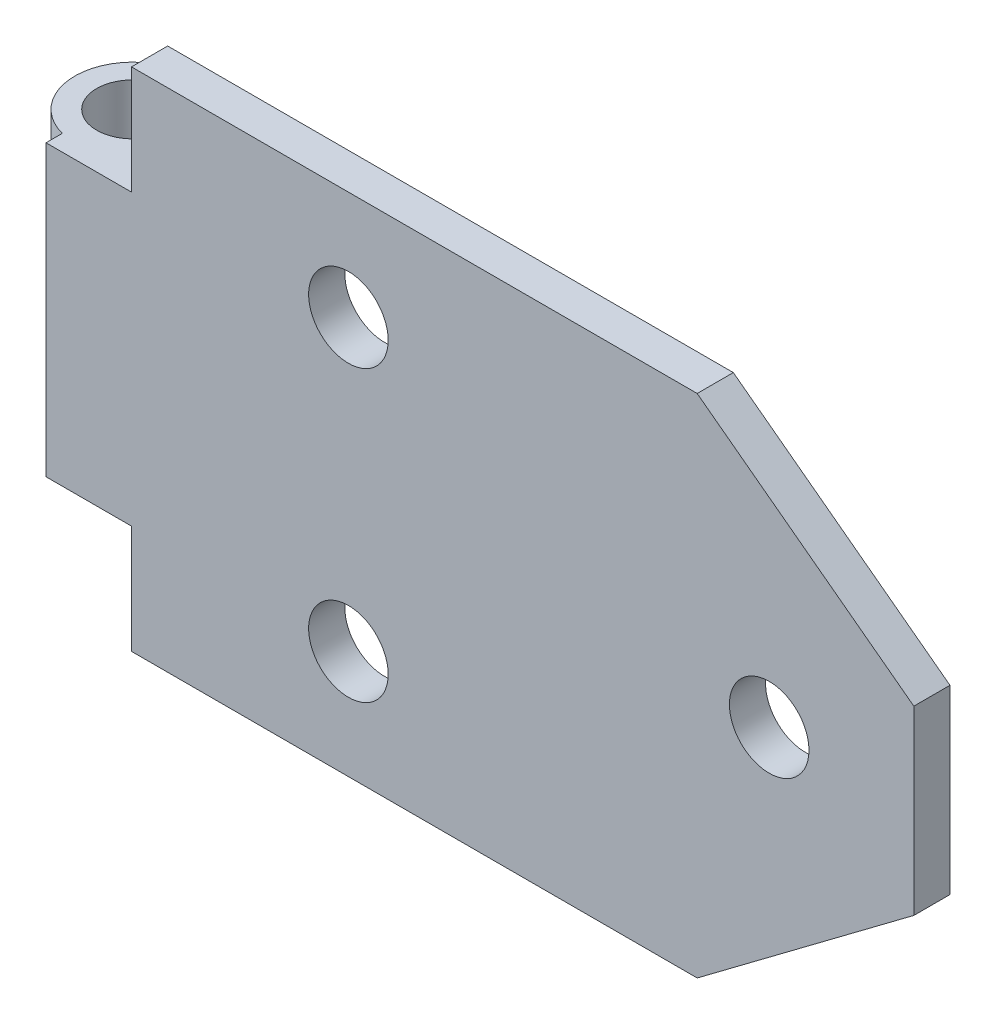
SolidWorks part; units mm, degrees
ref_plane "Front Plane" through (0, 0, 0) normal (0, 0, 1) x (1, 0, 0)
ref_plane "Top Plane" through (0, 0, 0) normal (0, 1, 0) x (1, 0, 0)
ref_plane "Right Plane" through (0, 0, 0) normal (1, 0, 0) x (0, 0, -1)
sketch "Sketch1" plane through (0, 0, 0) normal (0, 0, 1) x (1, 0, 0)
  line L1 (0, 15) -> (11.8238, 15)
  line L3 (11.8238, 55) -> (0, 55)
  line L5 (11.8238, 70) -> (90.0436, 70)
  line L6 (90.0436, 70) -> (120, 47.5327)
  line L7 (120, 47.5327) -> (120, 22.4673)
  line L8 (120, 22.4673) -> (90.0436, 0)
  line L9 (90.0436, 0) -> (11.8238, 0)
  line L10 (0, 55) -> (0, 15)
  line L11 (11.8238, 15) -> (11.8238, 0)
  line L12 (11.8238, 55) -> (11.8238, 70)
  circle A0 centre (41.815, 55) radius 5.5012
  circle A1 centre (41.815, 15) radius 5.5012
  circle A2 centre (100, 35) radius 5.5012
  dimension "D7" = 11.0024
  dimension "D2" = 70
  dimension "D3" = 11.8238
  dimension "D4" = 40
  dimension "D5" = 37.4455
  dimension "D6" = 25.0654
  dimension "D8" = 41.815
  dimension "D9" = 120
  dimension "D10" = 35
  dimension "D11" = 100
extrude "Boss-Extrude1" add sketch "Sketch1" along normal blind 5
sketch "Sketch2" plane through (0, 0, 0) normal (0, 1, 0) x (1, 0, 0)
  line L0 (90.0436, 0) -> (11.8238, 0) construction
  circle A0 centre (2, 5) radius 5
  circle A1 centre (2, 5) radius 8
  dimension "D1" = 10
  dimension "D2" = 2
  dimension "D3" = 3
extrude "Boss-Extrude2" add sketch "Sketch2" along normal blind 70
sketch "Sketch4" plane through (0, 0, 0) normal (0, 0, 1) x (1, 0, 0)
  line L0 (11.8238, 70) -> (-6, 70)
  line L1 (11.8238, 70) -> (11.8238, 55)
  line L2 (11.8238, 55) -> (-6, 55)
  line L3 (-6, 55) -> (-6, 70)
  line L4 (11.8238, 15) -> (11.8238, 0)
  line L5 (11.8238, 0) -> (-6, 0)
  line L6 (-6, 0) -> (-6, 15)
  line L7 (-6, 15) -> (11.8238, 15)
extrude "Cut-Extrude2" cut sketch "Sketch4" against normal through all both and the other way through all
